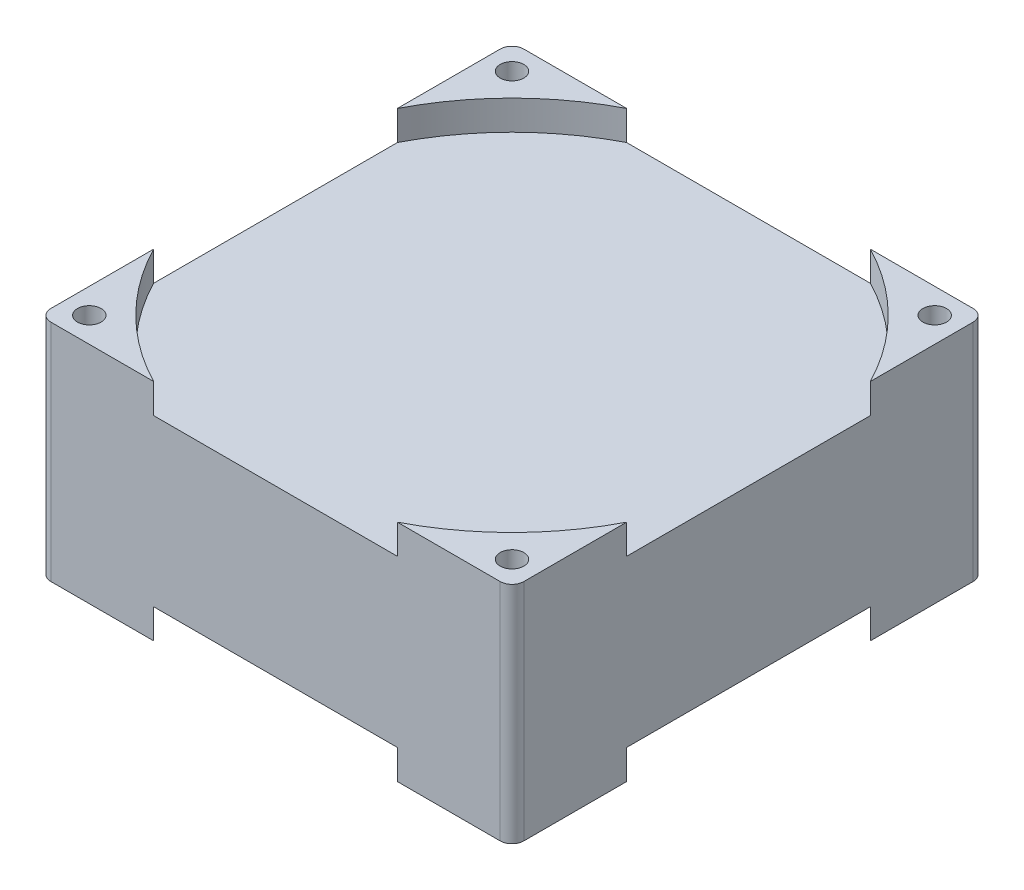
SolidWorks part; units mm, degrees
ref_plane "Front Plane" through (0, 0, 0) normal (0, 0, 1) x (1, 0, 0)
ref_plane "Top Plane" through (0, 0, 0) normal (0, 1, 0) x (1, 0, 0)
ref_plane "Right Plane" through (0, 0, 0) normal (1, 0, 0) x (0, 0, -1)
sketch "Sketch1" plane through (0, 0, 0) normal (0, 1, 0) x (1, 0, 0)
  line L1 (40, -40) -> (-40, -40)
  line L2 (40, -40) -> (40, 40)
  line L3 (40, 40) -> (-40, 40)
  line L4 (-40, -40) -> (-40, 40)
  line L5 (40, -40) -> (-40, 40) construction
  line L6 (40, 40) -> (-40, -40) construction
  point P0 (0, 0)
  dimension "D1" = 80
extrude "Body" add sketch "Sketch1" along normal blind 38 contours L3 L4 L1 L2
sketch "Sketch2" plane through (0, 38, 0) normal (0, 1, 0) x (1, 0, 0)
  line L1 (35.75, -35.75) -> (-35.75, -35.75) construction
  line L2 (35.75, -35.75) -> (35.75, 35.75) construction
  line L3 (35.75, 35.75) -> (-35.75, 35.75) construction
  line L4 (-35.75, -35.75) -> (-35.75, 35.75) construction
  line L5 (35.75, -35.75) -> (-35.75, 35.75) construction
  line L6 (35.75, 35.75) -> (-35.75, -35.75) construction
  circle A0 centre (-35.75, 35.75) radius 2
  circle A1 centre (35.75, 35.75) radius 2
  circle A2 centre (35.75, -35.75) radius 2
  circle A3 centre (-35.75, -35.75) radius 2
  point P8 (0, 0)
  dimension "D1" = 4
  dimension "D2" = 71.5
extrude "Cut-Extrude1" cut sketch "Sketch2" against normal blind 38
sketch "Sketch3" plane through (0, 38, 0) normal (0, 1, 0) x (1, 0, 0)
  line L0 (-40, 20.6155) -> (-40, -20.6155)
  line L1 (-40, -40) -> (-40, 40) construction
  line L2 (-20.6155, -40) -> (20.6155, -40)
  line L3 (40, -40) -> (-40, -40) construction
  line L4 (40, -20.6155) -> (40, 20.6155)
  line L5 (40, -40) -> (40, 40) construction
  line L6 (20.6155, 40) -> (-20.6155, 40)
  line L7 (40, 40) -> (-40, 40) construction
  arc A0 (-20.6155, 40) -> (-40, 20.6155) centre (0, 0) ccw
  arc A1 (40, 20.6155) -> (20.6155, 40) centre (0, 0) ccw
  arc A2 (20.6155, -40) -> (40, -20.6155) centre (0, 0) ccw
  arc A3 (-40, -20.6155) -> (-20.6155, -40) centre (0, 0) ccw
  dimension "D1" = 90
extrude "Cut-Extrude2" cut sketch "Sketch3" against normal blind 5
ref_plane "Plane1" through (0, 19, 0) normal (0, 1, 0) x (1, 0, 0)
mirror "Mirror1" about plane through (0, 19, 0) normal (0, 1, 0) of "Cut-Extrude2"
fillet "Fillet1" radius 2 4 edges at (-40, 19, 40) (40, 19, 40) (40, 19, -40) (-40, 19, -40)
sketch "Sketch4" plane through (-40, 0, 0) normal (-1, 0, 0) x (0, 0, 1)
  line L0 (-38, 16.5135) -> (40, 16.5135) construction
  line L1 (-38, 38) -> (-38, 0) construction
  line L2 (40, 38) -> (40, 0) construction
  text T0 "This is a fan" font "Century Gothic" height in points 36
extrude "Cut-Extrude3" cut sketch "Sketch4" against normal blind 1
